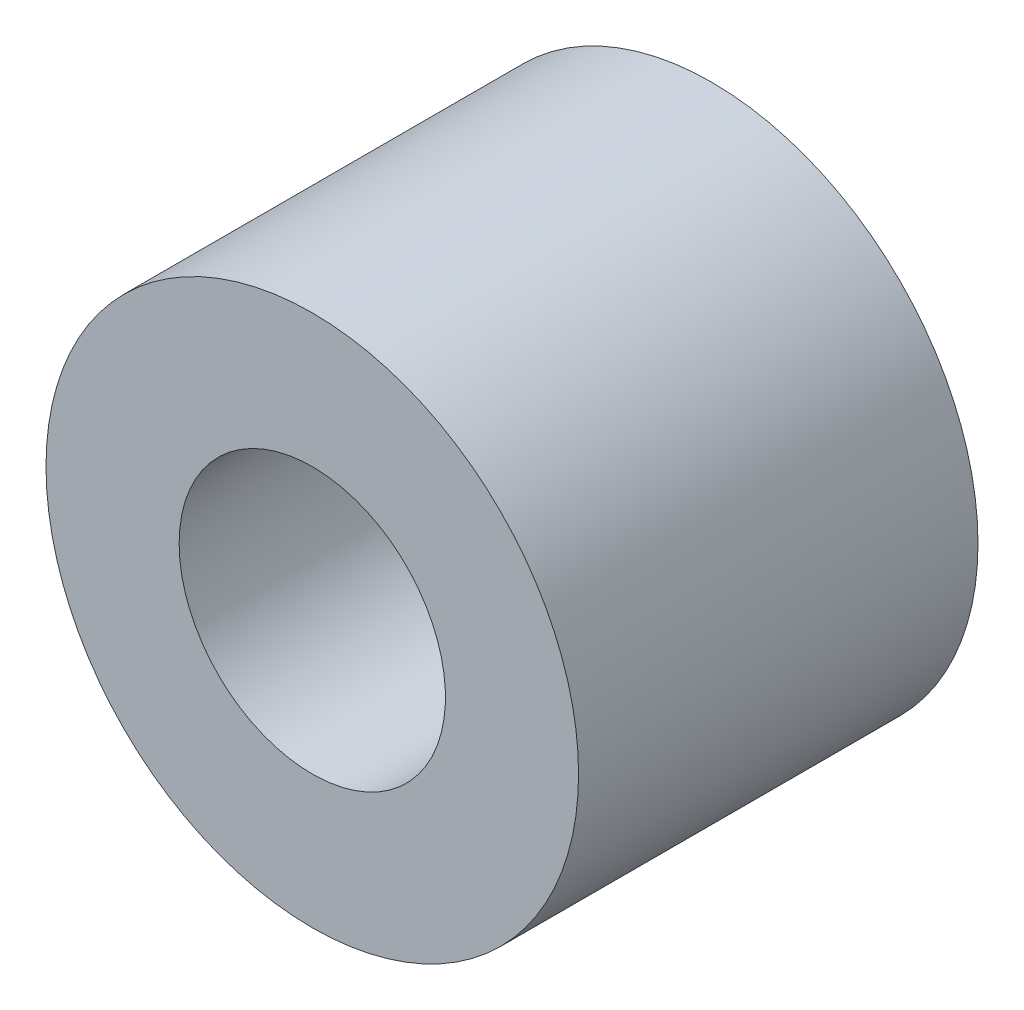
SolidWorks part; units mm, degrees
ref_plane "Front Plane" through (0, 0, 0) normal (0, 0, 1) x (1, 0, 0)
ref_plane "Top Plane" through (0, 0, 0) normal (0, 1, 0) x (1, 0, 0)
ref_plane "Right Plane" through (0, 0, 0) normal (1, 0, 0) x (0, 0, -1)
sketch "Sketch1" plane through (0, 0, 0) normal (0, 0, 1) x (1, 0, 0)
  circle A0 centre (0, 0) radius 1.5875
  circle A1 centre (0, 0) radius 3.175
  dimension "D1" = 6.35
  dimension "D2" = 3.175
extrude "Boss-Extrude1" add sketch "Sketch1" along normal blind 4.7625
scale "Scale1" scale about centroid uniform scaling yes scale factor 0.75
equation "\"large_diameter\" = 1/4in"
equation "\"small_diameter\" = 1/8in"
equation "\"arc_height\" = 1/32in"
equation "\"chain_space\" = 1/2in"
equation "\"chain_thickness\" = 1/32in"
equation "\"outer_height\" = 3/16in"
equation "\"inner_height\" = 2/16in"
equation "\"give\" = 1/64in"
equation "\"board_base\" = 10"
equation "\"board_rows\" = 3"
equation "\"num_links\"=4"
equation "\"D1@Sketch1\"=\"large_diameter\""
equation "\"D2@Sketch1\"=\"small_diameter\""
equation "\"D1@Boss-Extrude1\"=\"outer_height\""
